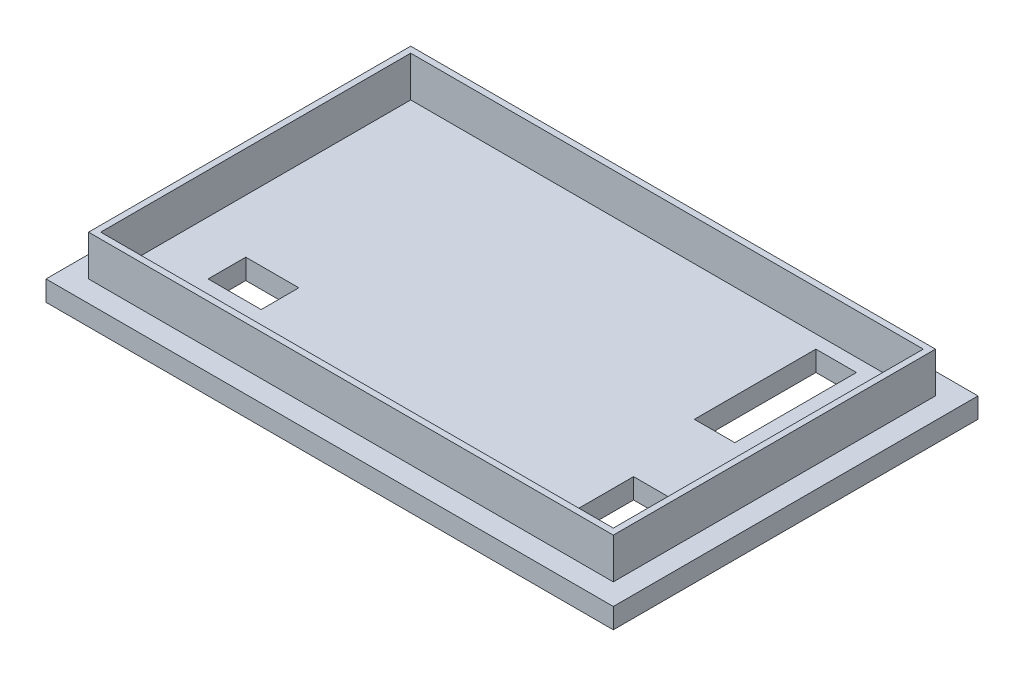
SolidWorks part; units mm, degrees
ref_plane "Alzado" through (0, 0, 0) normal (0, 0, 1) x (1, 0, 0)
ref_plane "Planta" through (0, 0, 0) normal (0, 1, 0) x (1, 0, 0)
ref_plane "Vista lateral" through (0, 0, 0) normal (1, 0, 0) x (0, 0, -1)
sketch "Croquis1" plane through (0, 0, 0) normal (0, 1, 0) x (1, 0, 0)
  line L1 (-70, 45) -> (70, 45)
  line L2 (-70, 45) -> (-70, -45)
  line L3 (-70, -45) -> (70, -45)
  line L4 (70, 45) -> (70, -45)
  line L5 (-70, 45) -> (70, -45) construction
  line L6 (-70, -45) -> (70, 45) construction
  point P0 (0, 0)
  dimension "D1" = 90
  dimension "D2" = 140
extrude "Saliente-Extruir1" add sketch "Croquis1" along normal blind 5
sketch "Croquis2" plane through (0, 5, 0) normal (0, 1, 0) x (1, 0, 0)
  line L1 (-64.75, 39.75) -> (64.75, 39.75)
  line L2 (-64.75, 39.75) -> (-64.75, -39.75)
  line L3 (-64.75, -39.75) -> (64.75, -39.75)
  line L4 (64.75, 39.75) -> (64.75, -39.75)
  line L5 (-64.75, 39.75) -> (64.75, -39.75) construction
  line L6 (-64.75, -39.75) -> (64.75, 39.75) construction
  line L7 (-63.25, 38.25) -> (63.25, 38.25)
  line L8 (-63.25, 38.25) -> (-63.25, -38.25)
  line L9 (-63.25, -38.25) -> (63.25, -38.25)
  line L10 (63.25, 38.25) -> (63.25, -38.25)
  line L11 (-63.25, 38.25) -> (63.25, -38.25) construction
  line L12 (-63.25, -38.25) -> (63.25, 38.25) construction
  point P0 (0, 0)
  point P6 (0, 0)
  dimension "D1" = 129.5
  dimension "D2" = 79.5
  dimension "D3" = 76.5
  dimension "D4" = 126.5
extrude "Saliente-Extruir2" add sketch "Croquis2" along normal blind 10
sketch "Croquis3" plane through (0, 5, 0) normal (0, 1, 0) x (1, 0, 0)
  line L0 (-64.75, -39.75) -> (64.75, -39.75) construction
  line L1 (44.75, -14.75) -> (59.75, -14.75)
  line L2 (44.75, -14.75) -> (44.75, -34.75)
  line L3 (44.75, -34.75) -> (59.75, -34.75)
  line L4 (59.75, -14.75) -> (59.75, -34.75)
  line L5 (44.75, -14.75) -> (59.75, -34.75) construction
  line L6 (44.75, -34.75) -> (59.75, -14.75) construction
  line L7 (64.75, -39.75) -> (64.75, 39.75) construction
  point P0 (52.25, -24.75)
  dimension "D1" = 20
  dimension "D2" = 15
  dimension "D3" = 5
  dimension "D4" = 5
extrude "Cortar-Extruir1" cut sketch "Croquis3" against normal through all
sketch "Croquis4" plane through (0, 0, 0) normal (0, -1, 0) x (1, 0, 0)
  line L0 (-70, 45) -> (70, 45) construction
  line L1 (-50, 25) -> (-36.9, 25)
  line L2 (-50, 25) -> (-50, 15.7)
  line L3 (-50, 15.7) -> (-36.9, 15.7)
  line L4 (-36.9, 25) -> (-36.9, 15.7)
  line L5 (-50, 25) -> (-36.9, 15.7) construction
  line L6 (-50, 15.7) -> (-36.9, 25) construction
  line L7 (-70, -45) -> (-70, 45) construction
  point P0 (-43.45, 20.35)
  dimension "D1" = 13.1
  dimension "D2" = 9.3
  dimension "D3" = 20
  dimension "D4" = 20
extrude "Cortar-Extruir2" cut sketch "Croquis4" against normal through all
sketch "Croquis5" plane through (0, 0, 0) normal (0, -1, 0) x (1, 0, 0)
  line L0 (70, 45) -> (70, -45) construction
  line L1 (40, -35) -> (50, -35)
  line L2 (40, -35) -> (40, -5)
  line L3 (40, -5) -> (50, -5)
  line L4 (50, -35) -> (50, -5)
  line L5 (40, -35) -> (50, -5) construction
  line L6 (40, -5) -> (50, -35) construction
  line L7 (70, -45) -> (-70, -45) construction
  point P0 (45, -20)
  dimension "D1" = 30
  dimension "D2" = 10
  dimension "D3" = 20
  dimension "D4" = 10
extrude "Cortar-Extruir3" cut sketch "Croquis5" against normal through all
